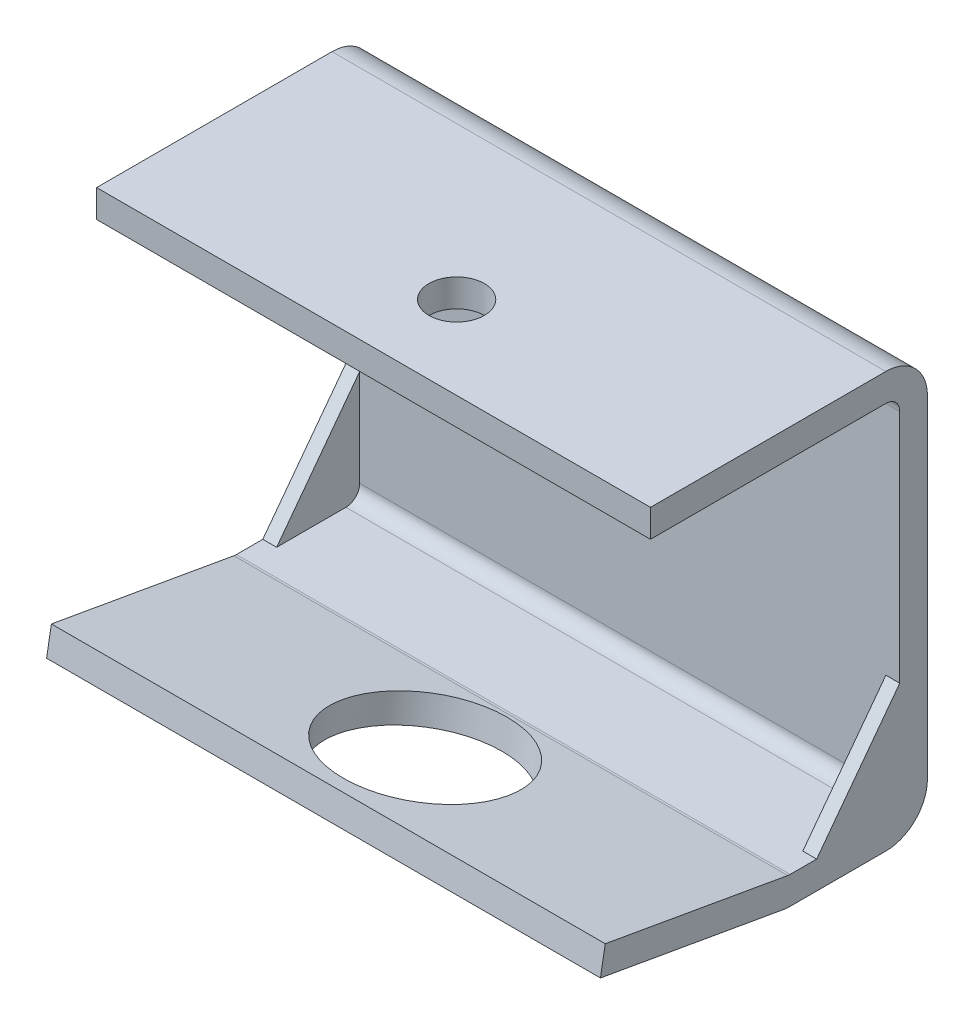
SolidWorks part; units mm, degrees
ref_plane "front" through (0, 0, 0) normal (0, 0, 1) x (1, 0, 0)
ref_plane "top" through (0, 0, 0) normal (0, 1, 0) x (1, 0, 0)
ref_plane "right" through (0, 0, 0) normal (1, 0, 0) x (0, 0, -1)
sketch "Sketch1" plane through (0, 0, 0) normal (1, 0, 0) x (0, 0, -1)
  line L0 (0, 0) -> (0, 82.55)
  line L1 (0, 82.55) -> (-57.15, 82.55)
  line L4 (-67.5238, 7.4276) -> (-25.4, 0)
  line L5 (-25.4, 0) -> (0, 0)
  dimension "D1" = 82.55
  dimension "D2" = 57.15
  dimension "D3" = 10
  dimension "D4" = 42.7736
  dimension "D5" = 25.4
extrude "Base-Extrude-Thin" add sketch "Sketch1" along normal mid plane 127 thin
sketch "Sketch2" plane through (0, 88.9, 0) normal (0, 1, 0) x (-1, 0, 0)
  line L0 (0, 50) -> (0, -50) construction
  line L1 (-63.5, 57.15) -> (63.5, 57.15) construction
  circle A0 centre (0, 38.1) radius 6.35
  dimension "D1" = 12.7
  dimension "D2" = 19.05
extrude "Cut-Extrude1" cut sketch "Sketch2" against normal up to next
sketch "Sketch3" plane through (63.5, 0, 0) normal (1, 0, 0) x (0, 0, -1)
  line L0 (-25.1222, 0) -> (-3.175, 0) construction
  line L1 (0, 3.175) -> (0, 79.375) construction
  line L2 (-19.05, 0) -> (-3.175, 0)
  line L3 (0, 3.175) -> (0, 25.4)
  line L4 (-19.05, 0) -> (0, 25.4)
  arc A0 (-3.175, 0) -> (0, 3.175) centre (-3.175, 3.175) ccw construction
  arc A1 (-3.175, 0) -> (0, 3.175) centre (-3.175, 3.175) ccw
  dimension "D1" = 25.4
  dimension "D2" = 19.05
extrude "Boss-Extrude1" add sketch "Sketch3" against normal blind 3.175
mirror "Mirror1" about plane through (0, 0, 0) normal (1, 0, 0) of "Boss-Extrude1"
hole_wizard "Dégagement #00001" positions "Esquisse2" profile "Esquisse1" hole size "#0000" standard "Ansi Pouce"
sketch "Esquisse2" plane through (0, -4.3437, 0.7659) normal (0, 0.9848, -0.1736) x (-1, 0, 0)
  point P0 (-4.2065, 49.405)
sketch "Esquisse1" plane through (4.2065, 4.2354, 49.4204) normal (1, 0, 0) x (0, 0.1736, 0.9848)
  line L0 (0, 0) -> (0, 13.9809)
  line L1 (0, 13.9809) -> (12.7, 6.35)
  line L2 (12.7, 6.35) -> (12.7, 0)
  line L5 (12.7, 0) -> (0, 0)
  line L10 (0, 13.9809) -> (-12.7, 6.35) construction
  line L11 (0, -6.35) -> (0, 107.95) construction
  dimension "Diamètre du perçage" = 25.4
  dimension "Profondeur du perçage" = 6.35
  dimension "Angle de pointe" = 118
sketch "Esquisse3" plane through (0, -4.3437, 0.7659) normal (0, 0.9848, -0.1736) x (1, 0, 0)
  circle A0 centre (0, -45.2398) radius 19.05 construction
  circle A1 centre (0, -45.2398) radius 19.05
extrude "Enlèv. mat.-Extru.1" cut sketch "Esquisse3" against normal through all
